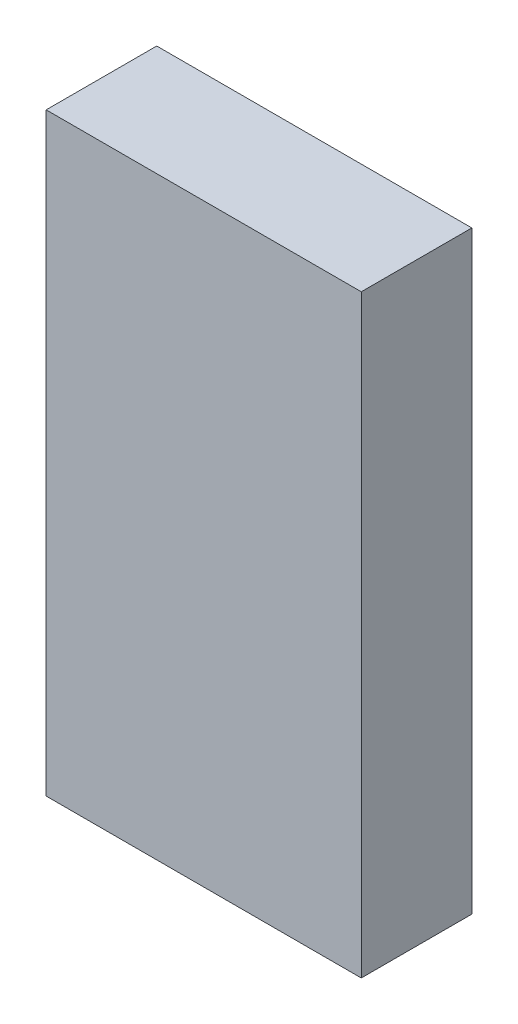
SolidWorks part; units mm, degrees
ref_plane "Front Plane" through (0, 0, 0) normal (0, 0, 1) x (1, 0, 0)
ref_plane "Top Plane" through (0, 0, 0) normal (0, 1, 0) x (1, 0, 0)
ref_plane "Right Plane" through (0, 0, 0) normal (1, 0, 0) x (0, 0, -1)
sketch "Sketch1" plane through (0, 0, 0) normal (0, 0, 1) x (1, 0, 0)
  line L1 (-57, 107.5) -> (57, 107.5)
  line L2 (-57, 107.5) -> (-57, -107.5)
  line L3 (-57, -107.5) -> (57, -107.5)
  line L4 (57, 107.5) -> (57, -107.5)
  line L5 (-57, 107.5) -> (57, -107.5) construction
  line L6 (-57, -107.5) -> (57, 107.5) construction
  point P0 (0, 0)
  dimension "D1" = 215
  dimension "D2" = 114
extrude "Boss-Extrude1" add sketch "Sketch1" along normal blind 40
sketch "Sketch2" plane through (0, 0, 0) normal (0, 0, -1) x (-1, 0, 0)
  line L0 (0, 107.5) -> (0, -107.5) construction
  line L1 (-57, 107.5) -> (57, 107.5) construction
  line L2 (57, -107.5) -> (-57, -107.5) construction
  line L3 (-57, 0) -> (57, 0) construction
  line L4 (-57, -107.5) -> (-57, 107.5) construction
  line L5 (57, 107.5) -> (57, -107.5) construction
  line L7 (-25, 75) -> (25, 75) construction
  line L8 (-25, 75) -> (-25, -75) construction
  line L9 (-25, -75) -> (25, -75) construction
  line L10 (25, 75) -> (25, -75) construction
  line L11 (-25, 75) -> (25, -75) construction
  line L12 (-25, -75) -> (25, 75) construction
  circle A0 centre (-25, 75) radius 2.5
  circle A1 centre (25, 75) radius 2.5
  circle A2 centre (25, -75) radius 2.5
  circle A3 centre (-25, -75) radius 2.5
  point P12 (0, 0)
  dimension "D3" = 5
  dimension "D1" = 50
  dimension "D2" = 150
extrude "Cut-Extrude1" cut sketch "Sketch2" against normal blind 30
